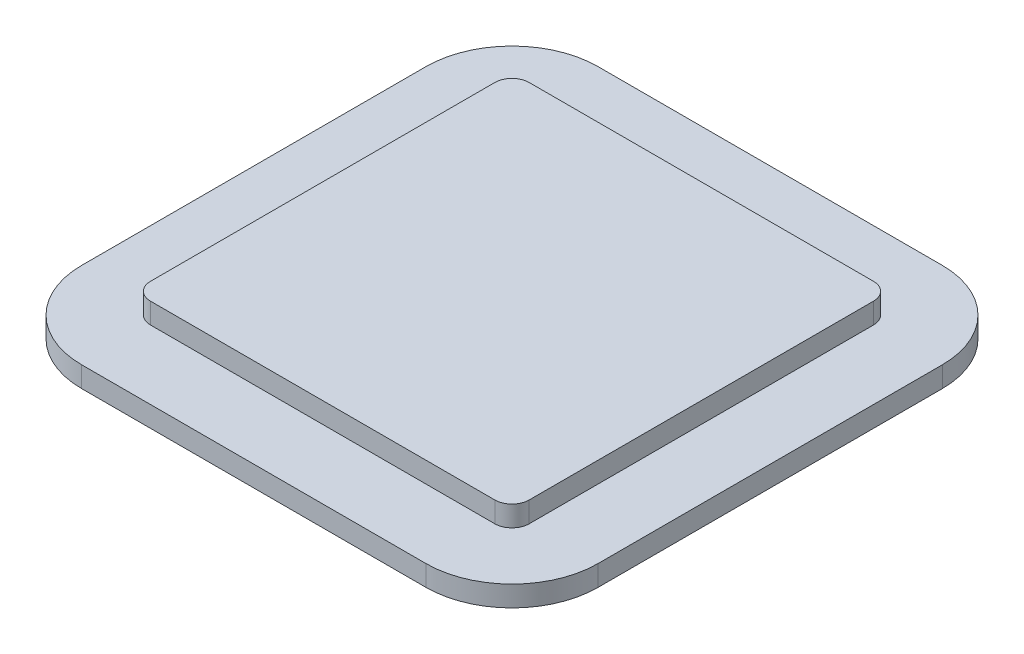
SolidWorks part; units mm, degrees
ref_plane "前视基准面" through (0, 0, 0) normal (0, 0, 1) x (1, 0, 0)
ref_plane "上视基准面" through (0, 0, 0) normal (0, 1, 0) x (1, 0, 0)
ref_plane "右视基准面" through (0, 0, 0) normal (1, 0, 0) x (0, 0, -1)
other "Configuration Table"
sketch "草图1" plane through (0, 0, 0) normal (0, 1, 0) x (1, 0, 0)
  line L1 (45.995, 36.2189) -> (60.995, 36.2189)
  line L2 (45.995, 36.2189) -> (45.995, 21.2189)
  line L3 (45.995, 21.2189) -> (60.995, 21.2189)
  line L4 (60.995, 36.2189) -> (60.995, 21.2189)
  dimension "D1" = 15
  dimension "D2" = 15
extrude "凸台-拉伸1" add sketch "草图1" along normal blind 0.6
fillet "圆角1" radius 2.5 4 edges at (60.995, 0.3, -36.2189) (45.995, 0.3, -36.2189) (60.995, 0.3, -21.2189) (45.995, 0.3, -21.2189)
sketch "草图2" plane through (0, 0.6, 0) normal (0, 1, 0) x (1, 0, 0)
  line L0 (45.995, 33.7189) -> (45.995, 23.7189) construction
  line L1 (47.995, 34.2189) -> (58.995, 34.2189)
  line L2 (47.995, 34.2189) -> (47.995, 23.2189)
  line L3 (47.995, 23.2189) -> (58.995, 23.2189)
  line L4 (58.995, 34.2189) -> (58.995, 23.2189)
  line L5 (58.495, 36.2189) -> (48.495, 36.2189) construction
  line L6 (60.995, 23.7189) -> (60.995, 33.7189) construction
  line L7 (48.495, 21.2189) -> (58.495, 21.2189) construction
  dimension "D1" = 2
  dimension "D2" = 2
  dimension "D3" = 2
  dimension "D4" = 2
extrude "凸台-拉伸2" add sketch "草图2" along normal blind 0.6
fillet "圆角2" radius 0.5 4 edges at (58.995, 0.9, -34.2189) (47.995, 0.9, -34.2189) (58.995, 0.9, -23.2189) (47.995, 0.9, -23.2189)
